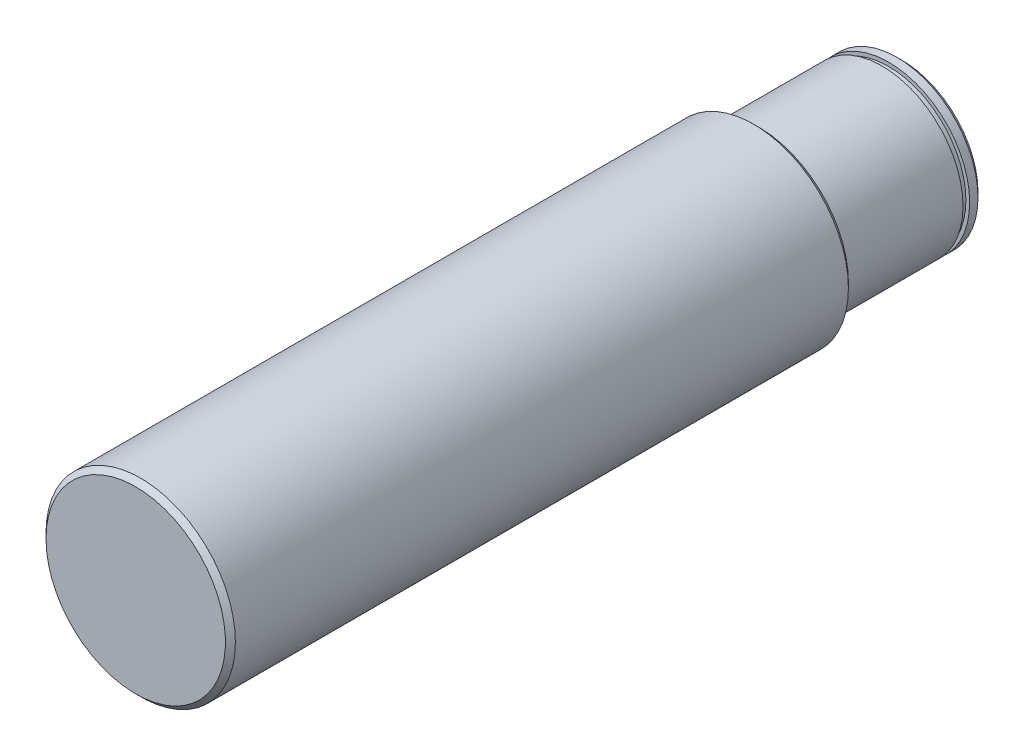
SolidWorks part; units mm, degrees
material "09Г2С ГОСТ 4543-71"
ref_plane "Спереди" through (0, 0, 0) normal (0, 0, 1) x (1, 0, 0)
ref_plane "Сверху" through (0, 0, 0) normal (0, 1, 0) x (1, 0, 0)
ref_plane "Справа" through (0, 0, 0) normal (1, 0, 0) x (0, 0, -1)
sketch "Эскиз1" plane through (0, 0, 0) normal (1, 0, 0) x (0, 0, -1)
  line L2 (0, 0) -> (0, 38)
  line L3 (0, 38) -> (250, 38)
  line L4 (250, 38) -> (250, 32.5)
  line L5 (250, 32.5) -> (299.5, 32.5)
  line L6 (307.5, 32.5) -> (307.5, 0)
  line L9 (0, 0) -> (307.5, 0)
  line L10 (0, 0) -> (-49.1534, 0) construction
  line L11 (299.5, 32.5) -> (299.5, 31)
  line L12 (299.5, 31) -> (302.15, 31)
  line L13 (302.15, 31) -> (302.15, 32.5)
  line L14 (302.15, 32.5) -> (307.5, 32.5)
  dimension "D1" = 76
  dimension "D2" = 65
  dimension "D3" = 5.35
  dimension "D4" = 2.65
  dimension "D5" = 62
  dimension "D7" = 57.5
  dimension "D8" = 250
revolve "Повернуть1" add sketch "Эскиз1" angle 360 about L9
chamfer "Фаска1" distance 2 angle 45 3 edges at (32.5, 0, -307.5) (38, 0, 0) (38, 0, -250)
